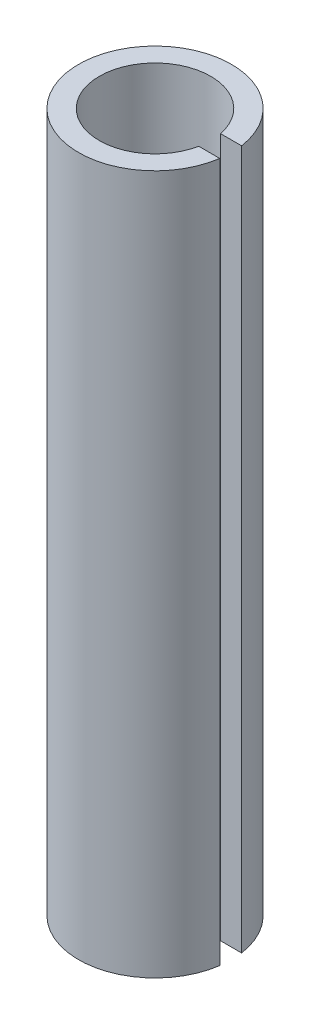
SolidWorks part; units mm, degrees
ref_plane "Front Plane" through (0, 0, 0) normal (0, 0, 1) x (1, 0, 0)
ref_plane "Top Plane" through (0, 0, 0) normal (0, 1, 0) x (1, 0, 0)
ref_plane "Right Plane" through (0, 0, 0) normal (1, 0, 0) x (0, 0, -1)
sketch "Sketch1" plane through (0, 0, 0) normal (0, 1, 0) x (1, 0, 0)
  line L0 (2.5005, 0.5) -> (3.4641, 0.5)
  line L1 (2.5005, -0.5) -> (3.4641, -0.5)
  line L2 (0, 0) -> (3.5, 0) construction
  circle A0 centre (0, 0) radius 3.5
  circle A1 centre (0, 0) radius 2.55
  dimension "D1" = 5.1
  dimension "D2" = 7
  dimension "D3" = 1
  dimension "D4" = 0.5
extrude "Boss-Extrude1" add sketch "Sketch1" along normal blind 32 contours A1 L0 A0 L1
